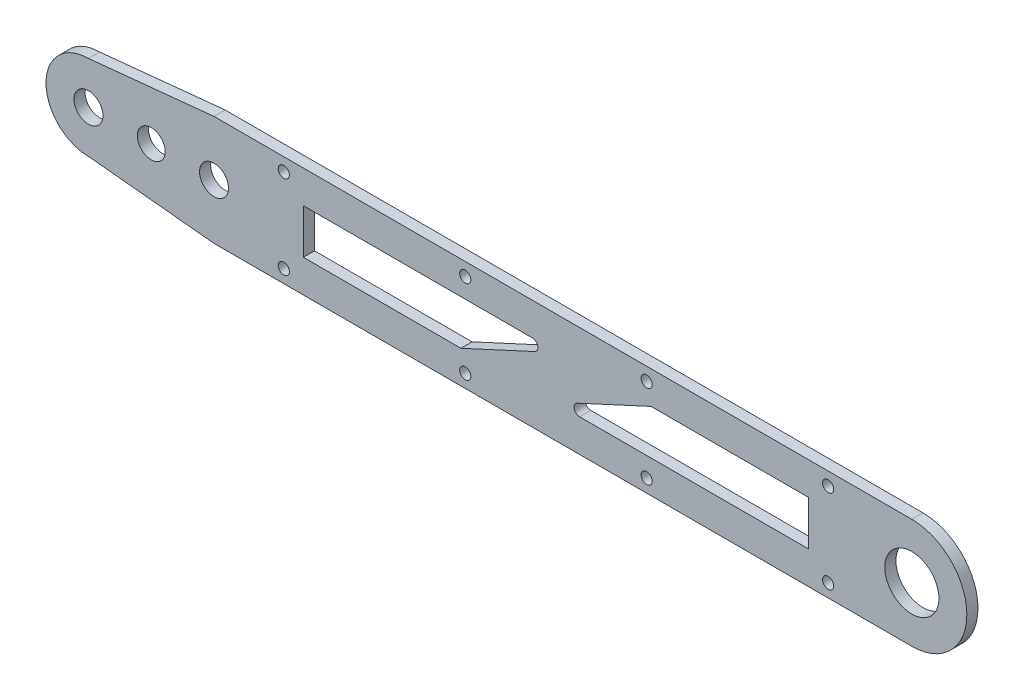
SolidWorks part; units mm, degrees
ref_plane "前视基准面" through (0, 0, 0) normal (0, 0, 1) x (1, 0, 0)
ref_plane "上视基准面" through (0, 0, 0) normal (0, 1, 0) x (1, 0, 0)
ref_plane "右视基准面" through (0, 0, 0) normal (1, 0, 0) x (0, 0, -1)
sketch "草图1" plane through (0, 0, 0) normal (0, 0, 1) x (1, 0, 0)
  line L0 (0, 0) -> (250, 0) construction
  line L1 (0, 0) -> (0, 15.4343) construction
  line L6 (0, 0) -> (0, -15.4343) construction
  line L7 (0, 0) -> (-45, 0) construction
  line L12 (250, 19.7) -> (0, 19.7)
  line L13 (0, 19.7) -> (-45, 15.2)
  line L14 (-45, -15.2) -> (0, -19.7)
  line L15 (0, -19.7) -> (250, -19.7)
  circle A0 centre (0, 0) radius 5.2
  circle A1 centre (250, 0) radius 9.7
  circle A2 centre (-45, 0) radius 5.2
  circle A3 centre (250, 0) radius 19.7 construction
  circle A4 centre (0, 0) radius 19.7 construction
  circle A5 centre (-45, 0) radius 15.2 construction
  arc A6 (-45, -15.2) -> (-45, 15.2) centre (-45, 0) cw
  arc A7 (250, -19.7) -> (250, 19.7) centre (250, 0) ccw
  dimension "D1" = 250
  dimension "D2" = 19.4
  dimension "D3" = 10.4
  dimension "D6" = 10
  dimension "D4" = 45
extrude "凸台-拉伸1" add sketch "草图1" along normal blind 4
sketch "草图2" plane through (0, 0, 4) normal (0, 0, 1) x (1, 0, 0)
  line L0 (0, 0) -> (250, 0) construction
  line L1 (0, 0) -> (0, -8.921) construction
  circle A0 centre (25, 15) radius 2
  circle A1 centre (90, 15) radius 2
  circle A2 centre (155, 15) radius 2
  circle A3 centre (220, 15) radius 2
  circle A4 centre (90, -15) radius 2
  circle A5 centre (155, -15) radius 2
  circle A6 centre (220, -15) radius 2
  circle A7 centre (25, -15) radius 2
  dimension "D1" = 4
  dimension "D2" = 15
  dimension "D3" = 25
  dimension "D4" = 4
  dimension "D5" = 2
extrude "切除-拉伸1" cut sketch "草图2" against normal blind 10
sketch "草图3" plane through (0, 0, 4) normal (0, 0, 1) x (1, 0, 0)
  line L4 (-45, 0) -> (0, 0) construction
  line L8 (32, 8) -> (32, -8)
  line L9 (32, -8) -> (88.4625, -8)
  line L10 (88.4625, -8) -> (114.8614, 4.1841)
  line L11 (114.0233, 8) -> (32, 8)
  line L17 (156.5375, 8) -> (213, 8)
  line L18 (213, 8) -> (213, -8)
  line L19 (213, -8) -> (130.9767, -8)
  line L20 (130.1386, -4.1841) -> (156.5375, 8)
  arc A2 (130.9767, -8) -> (130.1386, -4.1841) centre (130.9767, -6) cw
  arc A3 (114.8614, 4.1841) -> (114.0233, 8) centre (114.0233, 6) ccw
  circle A4 centre (-22.5, 0) radius 5
  point P6 (-22.5, 0)
  dimension "D1" = 2
extrude "切除-拉伸2" cut sketch "草图3" against normal blind 10
